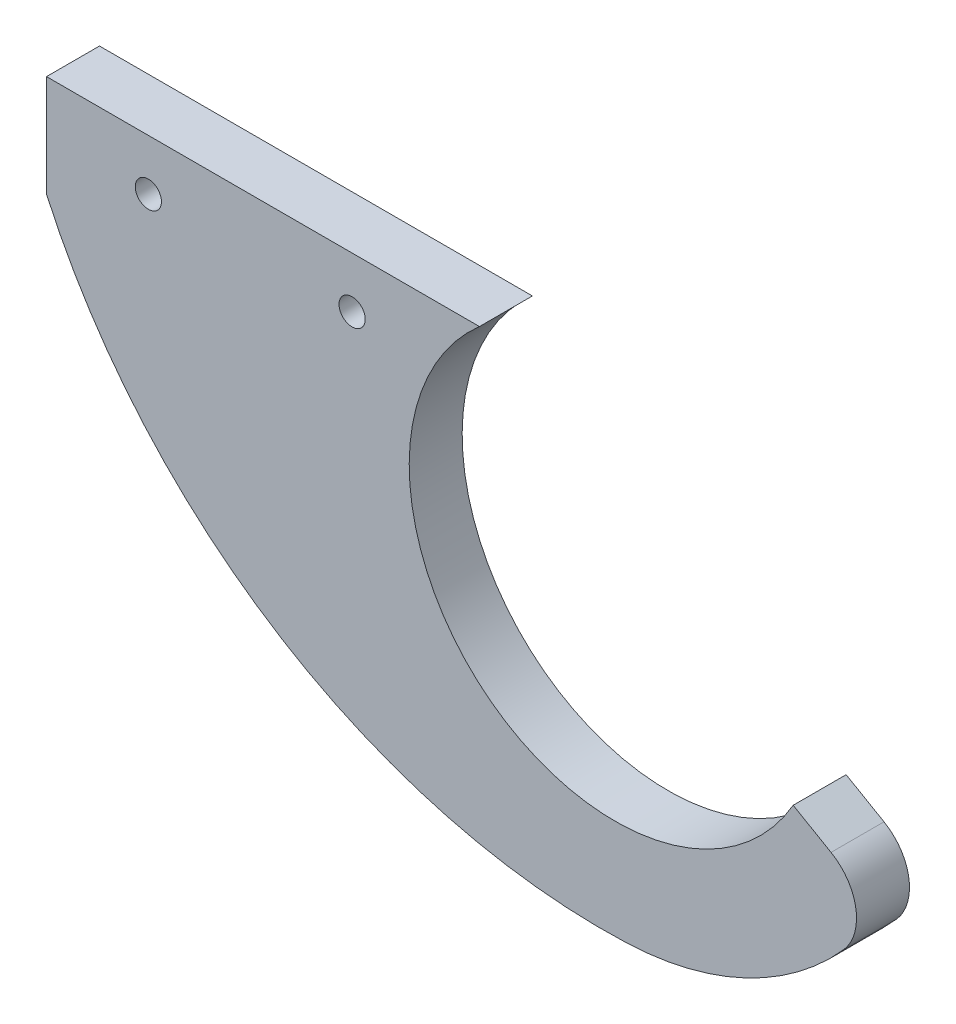
SolidWorks part; units mm, degrees
material "Acrylic (Blue)"
ref_plane "Front Plane" through (0, 0, 0) normal (0, 0, 1) x (1, 0, 0)
ref_plane "Top Plane" through (0, 0, 0) normal (0, 1, 0) x (1, 0, 0)
ref_plane "Right Plane" through (0, 0, 0) normal (1, 0, 0) x (0, 0, -1)
sketch "Sketch1" plane through (0, 0, 0) normal (0, 0, 1) x (1, 0, 0)
  line L0 (0, 0) -> (24.868, 0) construction
  line L1 (0, 0) -> (-101.6, 0) construction
  line L2 (0, 0) -> (0, -5.08) construction
  line L3 (0, -5.08) -> (-101.6, -5.08) construction
  line L4 (-101.6, 0) -> (-101.6, -5.08) construction
  line L5 (-53.975, -5.08) -> (-53.975, -17.78)
  line L6 (-6.35, -5.08) -> (0, -5.08)
  line L7 (16.8963, -24.384) -> (18.3684, -62.4555) construction
  line L8 (39.1133, -37.211) -> (49.8918, -43.434)
  line L9 (-53.975, -5.08) -> (-6.35, -5.08)
  line L10 (39.1133, -37.211) -> (16.8963, -24.384) construction
  line L11 (16.8963, -24.384) -> (89.4592, -24.384) construction
  line L12 (16.8963, -24.384) -> (-5.3208, -11.557) construction
  circle A0 centre (16.8963, -24.384) radius 25.654 construction
  arc A1 (49.8918, -43.434) -> (18.3684, -62.4555) centre (16.8963, -24.384) cw
  arc A2 (39.1133, -37.211) -> (0, -5.08) centre (16.8963, -24.384) cw
  arc A3 (-53.975, -17.78) -> (18.3684, -62.4555) centre (15.4241, 13.6875) ccw
  line B0 (-40.1828, -5.08) -> (-40.1828, -11.43) construction
  line B1 (-40.1828, -11.43) -> (-42.4688, -11.43) construction
  line B2 (-42.4688, -11.43) -> (-42.4688, -17.3736) construction
  line B3 (-42.4688, -17.3736) -> (-40.1828, -17.3736) construction
  line B4 (-40.1828, -17.3736) -> (-40.1828, -20.574) construction
  line B5 (-40.1828, -20.574) -> (-36.0172, -20.574) construction
  line B6 (-36.0172, -20.574) -> (-36.0172, -17.3736) construction
  line B7 (-36.0172, -17.3736) -> (-33.7312, -17.3736) construction
  line B8 (-33.7312, -17.3736) -> (-33.7312, -11.43) construction
  line B9 (-33.7312, -11.43) -> (-36.0172, -11.43) construction
  line B10 (-36.0172, -11.43) -> (-36.0172, -5.08) construction
  line B11 (-36.0172, -5.08) -> (-31.75, -5.08) construction
  line B12 (-31.75, -5.08) -> (-31.75, -0.254) construction
  line B13 (-31.75, -0.254) -> (-25.4, -0.254) construction
  line B14 (-25.4, -0.254) -> (-25.4, -5.08) construction
  line B15 (-40.1828, -5.08) -> (-44.45, -5.08) construction
  line B16 (-44.45, -5.08) -> (-44.45, -0.254) construction
  line B17 (-44.45, -0.254) -> (-50.8, -0.254) construction
  line B18 (-50.8, -0.254) -> (-50.8, -5.08) construction
  line B19 (-36.0172, -5.08) -> (-40.1828, -5.08) construction
  line B20 (-6.35, -0.254) -> (-6.35, -5.08) construction
  line B21 (-21.1328, -5.08) -> (-21.1328, -11.43) construction
  line B22 (-21.1328, -11.43) -> (-23.4188, -11.43) construction
  line B23 (-23.4188, -11.43) -> (-23.4188, -17.3736) construction
  line B24 (-23.4188, -17.3736) -> (-21.1328, -17.3736) construction
  line B25 (-21.1328, -17.3736) -> (-21.1328, -20.574) construction
  line B26 (-21.1328, -20.574) -> (-16.9672, -20.574) construction
  line B27 (-16.9672, -20.574) -> (-16.9672, -17.3736) construction
  line B28 (-16.9672, -17.3736) -> (-14.6812, -17.3736) construction
  line B29 (-14.6812, -17.3736) -> (-14.6812, -11.43) construction
  line B30 (-14.6812, -11.43) -> (-16.9672, -11.43) construction
  line B31 (-16.9672, -11.43) -> (-16.9672, -5.08) construction
  line B32 (-16.9672, -5.08) -> (-12.7, -5.08) construction
  line B33 (-12.7, -5.08) -> (-12.7, -0.254) construction
  line B34 (-12.7, -0.254) -> (-6.35, -0.254) construction
  line B35 (-21.1328, -5.08) -> (-25.4, -5.08) construction
  line B36 (-25.4, -5.08) -> (-25.4, -0.254) construction
  line B37 (-25.4, -0.254) -> (-31.75, -0.254) construction
  line B38 (-31.75, -0.254) -> (-31.75, -5.08) construction
  line B39 (-16.9672, -5.08) -> (-21.1328, -5.08) construction
  dimension "D2" = 51.308
  dimension "D4" = 12.7
  dimension "D5" = 38.1
  dimension "D7" = 76.2
  dimension "D1" = 5.08
  dimension "D3" = 1.27
  dimension "D6" = 3.175
  dimension "D8" = 6.35
  dimension "D9" = 24.868
  dimension "D10" = 30
  dimension "D11" = 101.6
  dimension "D12" = 16.8963
sketch_block_instance "NUT_HOLE_2X-1"
sketch_block "NUT_HOLE_2X" parameters "D1"=6.35, "D2"=4.1656, "D3"=25.4, "D4"=4.826, "D5"=8.7376, "D6"=5.9436, "D7"=6.35, "D8"=20.32, "D9"=2
extrude "Boss-Extrude1" add sketch "Sketch1" along normal blind 6.604
fillet "Fillet1" radius 6.35 1 edges at (49.8918, -43.434, 3.302)
hole_wizard "#4 Clearance Hole1" positions "3DSketch1" profile "Sketch2" hole size "#4" standard "ANSI Inch"
sketch3d "3DSketch1"
  line L0 (-53.975, -5.08, 6.604) -> (-53.975, -17.78, 6.604) construction
  line L1 (-53.975, -5.08, 6.604) -> (0, -5.08, 6.604) construction
  point P0 (-15.875, -11.43, 6.604)
  point P7 (-41.275, -11.43, 6.604)
  dimension "D1" = 38.1
  dimension "D2" = 6.35
  dimension "D3" = 6.35
  dimension "D4" = 12.7
sketch "Sketch2" plane through (-15.875, -11.43, 6.604) normal (1, 0, 0) x (0, -1, 0)
  line L0 (0, 0) -> (0, 10.6326)
  line L1 (0, 10.6326) -> (1.6319, 9.652)
  line L2 (1.6319, 9.652) -> (1.6319, 0)
  line L5 (1.6319, 0) -> (0, 0)
  line L10 (0, 10.6326) -> (-1.6319, 9.652) construction
  line L11 (0, -6.35) -> (0, 107.95) construction
  dimension "Hole Dia." = 3.2639
  dimension "Hole Depth" = 9.652
  dimension "Drill Angle" = 118
